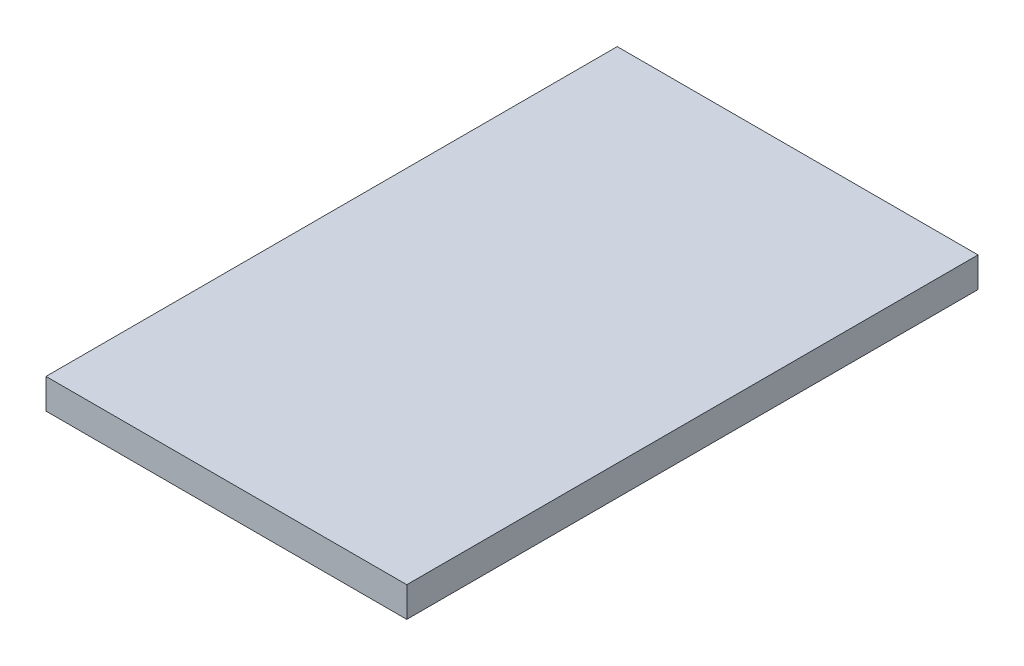
SolidWorks part; units mm, degrees
ref_plane "前视基准面" through (0, 0, 0) normal (0, 0, 1) x (1, 0, 0)
ref_plane "上视基准面" through (0, 0, 0) normal (0, 1, 0) x (1, 0, 0)
ref_plane "右视基准面" through (0, 0, 0) normal (1, 0, 0) x (0, 0, -1)
sketch "草图1" plane through (0, 0, 0) normal (0, 1, 0) x (1, 0, 0)
  line L1 (0, 0) -> (12, 0)
  line L2 (0, 0) -> (0, 19)
  line L3 (0, 19) -> (12, 19)
  line L4 (12, 0) -> (12, 19)
  dimension "D1" = 12
  dimension "D2" = 19
extrude "凸台-拉伸1" add sketch "草图1" along normal blind 1
